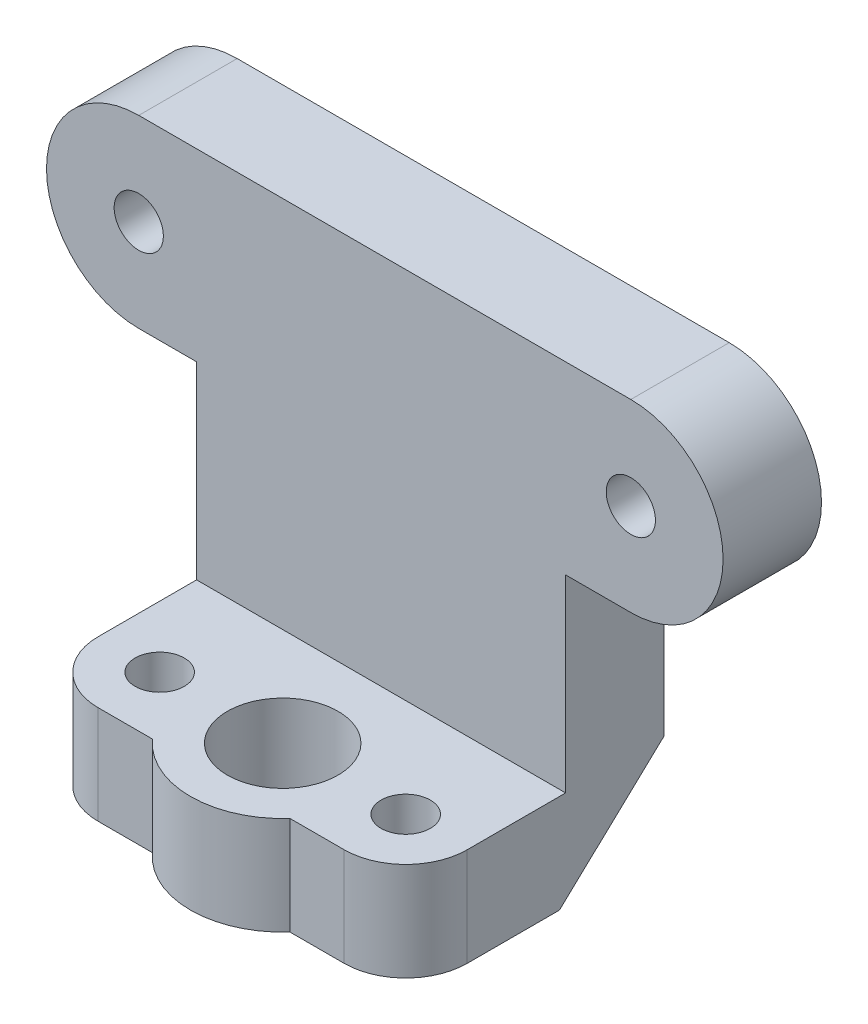
SolidWorks part; units mm, degrees
ref_plane "Front Plane" through (0, 0, 0) normal (0, 0, 1) x (1, 0, 0)
ref_plane "Top Plane" through (0, 0, 0) normal (0, 1, 0) x (1, 0, 0)
ref_plane "Right Plane" through (0, 0, 0) normal (1, 0, 0) x (0, 0, -1)
sketch "Sketch1" plane through (0, 0, 0) normal (0, 0, 1) x (1, 0, 0)
  line L0 (134.5, -11.9) -> (174.5, -11.9)
  line L1 (174.5, -26.9) -> (134.5, -26.9)
  arc A0 (134.5, -11.9) -> (134.5, -26.9) centre (134.5, -19.4) ccw
  arc A1 (174.5, -26.9) -> (174.5, -11.9) centre (174.5, -19.4) ccw
  circle A2 centre (134.5, -19.4) radius 2
  circle A3 centre (174.5, -19.4) radius 2
  dimension "D1" = 15
  dimension "D2" = 15
  dimension "D3" = 4
  dimension "D4" = 4
extrude "Boss-Extrude1" add sketch "Sketch1" along normal blind 8
sketch "Sketch2" plane through (0, -42.25, 0) normal (0, 1, 0) x (1, 0, 0)
  circle A0 centre (154.2, -16) radius 4.5
  circle A1 centre (154.2, -16) radius 7.5
  circle A2 centre (154.2, -16) radius 4 construction
  dimension "D1" = 15
  dimension "D2" = 0.5
extrude "Boss-Extrude2" add sketch "Sketch2" against normal blind 8 separate body
sketch "Sketch3" plane through (0, -42.25, 0) normal (0, 1, 0) x (1, 0, 0)
  line L0 (146.498, -16) -> (144.2, -16) construction
  line L1 (154.2, -16) -> (144.2, -16) construction
  line L2 (144.2, -11) -> (148.6098, -11)
  line L3 (144.2, -21) -> (148.6098, -21)
  line L4 (154.2, -16) -> (154.2, -18.2989) construction
  line L5 (161.902, -16) -> (164.2, -16) construction
  line L6 (161.902, -16) -> (164.2, -16) construction
  line L7 (164.2, -21) -> (159.7902, -21)
  line L8 (164.2, -11) -> (159.7902, -11)
  line L9 (146.498, -16) -> (144.2, -16) construction
  line L10 (146.498, -16) -> (144.2, -16) construction
  circle A0 centre (154.2, -16) radius 7.5 construction
  circle A1 centre (154.2, -16) radius 4.5 construction
  circle A2 centre (144.2, -16) radius 2
  arc A3 (144.2, -11) -> (144.2, -21) centre (144.2, -16) ccw
  arc A4 (148.6098, -11) -> (148.6098, -21) centre (154.2, -16) ccw
  arc A5 (159.7902, -11) -> (159.7902, -21) centre (154.2, -16) cw
  arc A6 (164.2, -11) -> (164.2, -21) centre (164.2, -16) cw
  circle A7 centre (164.2, -16) radius 2
  dimension "D2" = 4
  dimension "D3" = 5
  dimension "D1" = 10
extrude "Boss-Extrude3" add sketch "Sketch3" against normal blind 8
sketch "Sketch8" plane through (0, -26.9, 0) normal (0, -1, 0) x (-1, 0, 0)
  line L0 (-169.2, -8) -> (-169.2, 0)
  line L1 (-169.2, -16) -> (-169.2, 0) construction
  line L2 (-134.5, 0) -> (-174.5, 0) construction
  line L3 (-139.2, -16) -> (-139.2, 0) construction
  line L4 (-169.2, 0) -> (-139.2, 0)
  line L5 (-139.2, 0) -> (-139.2, -8)
  line L6 (-139.2, -8) -> (-169.2, -8)
  arc A0 (-164.2, -11) -> (-164.2, -21) centre (-164.2, -16) ccw construction
  arc A1 (-144.2, -21) -> (-144.2, -11) centre (-144.2, -16) ccw construction
extrude "Boss-Extrude7" add sketch "Sketch8" along normal up to surface (15.35 mm away) up to face at (154.2, -42.25, 20.5)
sketch "Sketch9" plane through (169.2, 0, 0) normal (1, 0, 0) x (0, 0, -1)
  line L0 (-8, -42.25) -> (-11, -42.25)
  line L1 (-11, -42.25) -> (-11, -50.25)
  line L2 (-11, -50.25) -> (-8.5, -50.25)
  line L3 (-8.5, -50.25) -> (0, -42.25)
  line L4 (0, -42.25) -> (-8, -42.25)
  line L5 (-8, -42.25) -> (-7.9465, -41.9509)
  line M2 (-8, -42.25) -> (0, -42.25)
extrude "Boss-Extrude8" add sketch "Sketch9" against normal up to surface (30 mm away) contours L2 L3 L0 L1 M2 up to face at (139.2, -34.575, 4)
sketch "Sketch10" plane through (0, -42.25, 0) normal (0, 1, 0) x (1, 0, 0)
  line L0 (139.2, -16) -> (139.2, -11)
  line L1 (139.2, -11) -> (144.2, -11)
  line L2 (144.2, -11) -> (139.2, -16)
  line L3 (139.2, -16) -> (139.4829, -15.9299)
  line L4 (154.2, -16) -> (154.2, -13.0837) construction
  line L5 (169.2, -16) -> (168.9171, -15.9299)
  line L6 (164.2, -11) -> (169.2, -16)
  line L7 (169.2, -11) -> (164.2, -11)
  line L8 (169.2, -16) -> (169.2, -11)
  line L9 (139.2, -16) -> (139.4829, -15.9299)
  arc A0 (144.2, -11) -> (144.2, -21) centre (144.2, -16) ccw construction
  line M4 (139.2, -11) -> (144.2, -11)
  arc M5 (144.2, -11) -> (144.2, -21) centre (144.2, -16) ccw
  arc M9 (164.2, -21) -> (164.2, -11) centre (164.2, -16) ccw
  line M10 (164.2, -11) -> (169.2, -11)
extrude "Boss-Extrude9" add sketch "Sketch10" against normal through all contours L0 M5 M4 | L8 M9 M10
equation "\"X-ROD-SPACING\"=45"
equation "\"Y-ROD-SPACING\"=75"
equation "\"Z-ROD-SPACING\"=17.5"
equation "\"Y-BED-OFFSET\"=2"
equation "\"Y-BED-ROD-INSET\"=3.5"
equation "\"Y-BED-SCREW-SPACING\"=209"
equation "\"Y-BED-SCREW-CUTOUT-SLOT-HEIGHT\"=2"
equation "\"T-SLOT-NUT-FILLET-RADIUS\"=0.25"
equation "\"T-SLOT-SCREW-SHAFT-RADIUS\"=1.75"
equation "\"T-SLOT-SCREW-SHAFT-CUTOUT-LENGTH\"=10.5"
equation "\"T-SLOT-NUT-DEPTH\"=4.2"
equation "\"T-SLOT-NUT-WIDTH\"=3"
equation "\"T-SLOT-NUT-END-DISTANCE\"=8"
equation "\"ACRYLIC-THICKNESS\"=10"
equation "\"ACRYLIC-THICKNESS2\"=4.5"
equation "\"ACRYLIC-TAB-CUTOUT-SIZE\"=\"ACRYLIC-THICKNESS\"+\"ACRYLIC-TAB-TOLERANCE\"*2"
equation "\"ACRYLIC-TAB-TOLERANCE\"=.1"
equation "\"ACRYLIC-TAB-WIDTH\"=\"ACRYLIC-THICKNESS\""
equation "\"ACRYLIC-M3-HOLE\"=3.1"
equation "\"SMOOTHROD-CAP-SCREW-DISTANCE\"=20"
equation "\"FRAME-WIDTH-INNER\"=370"
equation "\"NEMA17-HOLE-SPACING\"=31"
equation "\"NEMA17-CENTRAL-CUTOUT\"=22.5"
equation "\"Z-BRACKET-REACH\"=55"
equation "\"Z-ROD-INSET\"=16"
equation "\"TOP-BRACKET-SPACING\"=40"
equation "\"SMOOTHROD-X-LENGTH\"=350"
equation "\"SMOOTHROD-Y-LENGTH\"=350"
equation "\"SMOOTHROD-Z-LENGTH\"=350"
equation "\"SMOOTHROD-TIGHTENING-HEADROOM\"=.25"
equation "\"LEADSCREW-Z-LENGTH\"=300"
equation "\"SCREW-LENGTH-FRAME\"=\"ACRYLIC-THICKNESS\" + 10"
equation "\"SCREW-LENGTH-MOTOR\"=\"ACRYLIC-THICKNESS\" + 5"
equation "\"SCREW-LENGTH-EXTRUDER\"=28"
equation "\"SCREW-HEAD-RADIUS\"=6"
equation "\"PRINTED-M3-HOLE\"=3.5"
equation "\"PRINTED-X-SMOOTHROD-DIAMETER\"=8.2"
equation "\"PRINTED-X-SMOOTHROD-CUTOUT\"=10"
equation "\"PRINTED-X-BASE-HEIGHT\"=10"
equation "\"PRINTED-LM8UU-CUTOUT-SIZE\"=15.25"
equation "\"PRINTED-LM8UU-CUTOUT-LENGTH\"=24.5"
equation "\"PRINTED-X-IDLER-HEIGHT\"=16"
equation "\"PRINTED-M3-NUT-AF\"=6.25"
equation "\"PSU-MOUNTING-WIDTH\"=95"
equation "\"PSU-MOUNTING-HEIGHT\"=177"
equation "\"Y-BELT-TO-ROD-DISTANCE\"=20"
equation "\"SPOOL-HOLDER-ROD-SPACING\"=150"
equation "\"ACRYLIC-X-CARRIAGE-WIDTH\"=55"
equation "\"ACRYLIC-X-CARRIAGE-HEIGHT\"=75"
equation "\"ACRYLIC-X-CARRIAGE-LM8UU-CUTOUT-WIDTH\"=24.25"
equation "\"ACRYLIC-X-CARRIAGE-LM8UU-CUTOUT-HEIGHT\"=11.5"
equation "\"ACRYLIC-X-CARRIAGE-SCREW-SPACING-X\"=15"
equation "\"ACRYLIC-X-CARRIAGE-SCREW-SPACING-Y\"=33"
equation "\"ACRYLIC-X-CARRIAGE-CENTER-TAB-SPACING\"=14"
equation "\"ACRYLIC-X-CARRIAGE-EXTRUDER-OFFSET\"=26"
equation "\"ACRYLIC-X-CARRIAGE-EXTRUDER-ANGLE\"=90"
equation "\"ACRYLIC-X-CARRIAGE-EXTRUDER-SHELF-DEPTH\"=\"ACRYLIC-X-CARRIAGE-EXTRUDER-OFFSET\" + 28"
equation "\"ACRYLIC-X-CARRIAGE-EXTRUDER-BRACE-SPACING\"=23"
equation "\"ACRYLIC-X-CARRIAGE-EXTRUDER-BRACE-TAB-OFFSET\"=20"
equation "\"ACRYLIC-X-CARRIAGE-EXTRUDER-BRACE-HEIGHT\"=35"
equation "\"ACRYLIC-X-CARRIAGE-EXTRUDER-BRACE-SCREW-SPACING\"=22"
equation "\"ACRYLIC-X-CARRIAGE-DUAL-WIDTH-MULTIPLIER\"=1.65"
equation "\"ACRYLIC-X-CARRIAGE-DUAL-HOTEND-SPACING\"=42"
equation "\"ACRYLIC-X-CARRIAGE-DUAL-WIDTH\"=75"
equation "\"ACRYLIC-X-CARRIAGE-DUAL-FAN-OFFSET\"=52"
equation "\"ACRYLIC-X-CARRIAGE-DUAL-FAN-HEIGHT\"=20"
equation "\"ACRYLIC-X-CARRIAGE-DUAL-HOTEND-SEPARATION\"=36"
equation "\"ACRYLIC-X-CARRIAGE-DUAL-MOUNT-PLATE-DEPTH\"=75"
equation "\"ACRYLIC-X-CARRIAGE-DUAL-MOUNT-BRACE-WIDTH\"=33"
equation "\"ACRYLIC-X-CARRIAGE-DUAL-MOUNT-SCREW-WIDTH\"=40"
equation "\"BLOWER-FAN-WIDTH\"=15"
equation "\"D2@Boss-Extrude2\"=\"SMOOTHROD-TIGHTENING-HEADROOM\""
equation "\"D1@Sketch3\"=\"SMOOTHROD-CAP-SCREW-DISTANCE\"/2"
